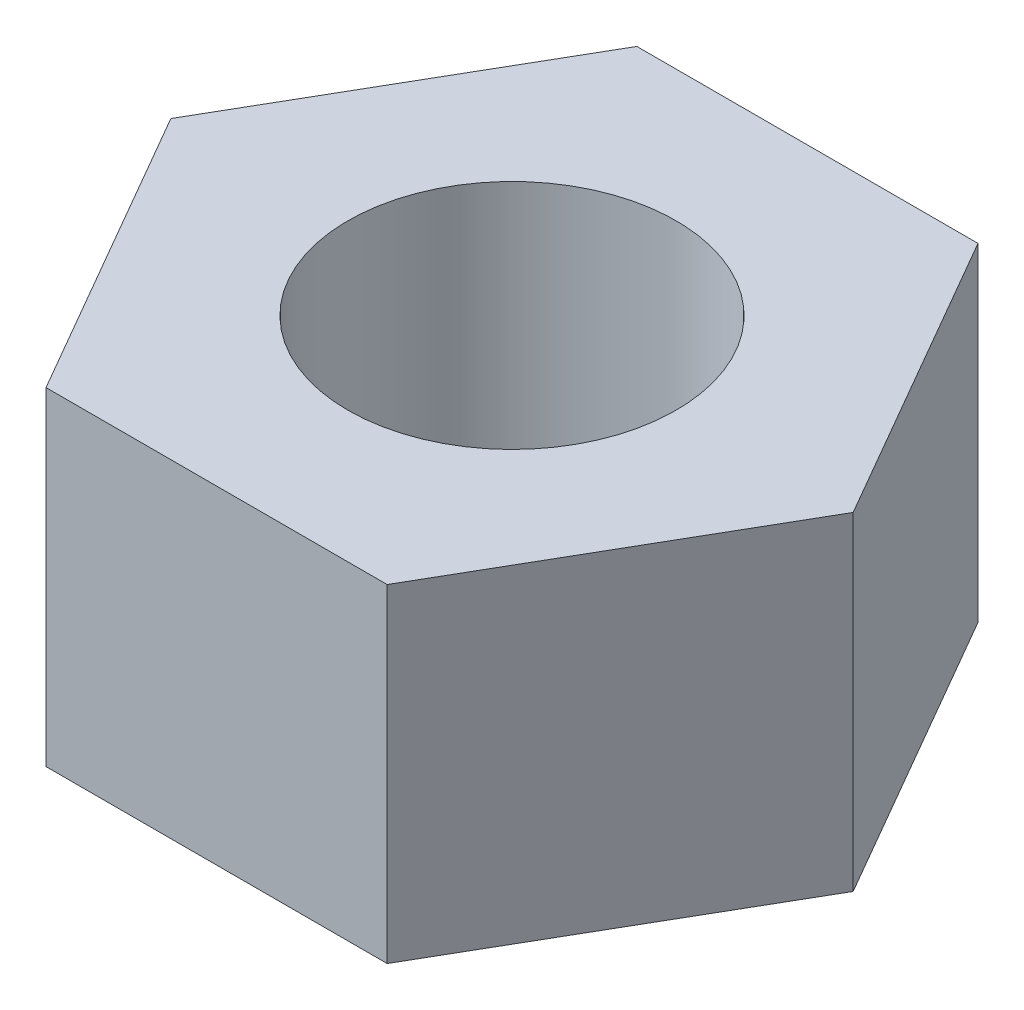
SolidWorks part; units mm, degrees
material "Plain Carbon Steel"
ref_plane "Front Plane" through (0, 0, 0) normal (0, 0, 1) x (1, 0, 0)
ref_plane "Top Plane" through (0, 0, 0) normal (0, 1, 0) x (1, 0, 0)
ref_plane "Right Plane" through (0, 0, 0) normal (1, 0, 0) x (0, 0, -1)
sketch "Sketch1" plane through (0, 0, 0) normal (0, 1, 0) x (1, 0, 0)
  line L1 (5.1962, 9) -> (-5.1962, 9)
  line L2 (-5.1962, 9) -> (-10.3923, 0)
  line L3 (-10.3923, 0) -> (-5.1962, -9)
  line L4 (-5.1962, -9) -> (5.1962, -9)
  line L5 (5.1962, -9) -> (10.3923, 0)
  line L6 (10.3923, 0) -> (5.1962, 9)
  circle A0 centre (0, 0) radius 9 construction
  circle A1 centre (0, 0) radius 5
  dimension "D1" = 10
  dimension "D2" = 18
extrude "Boss-Extrude1" add sketch "Sketch1" along normal mid plane 10
